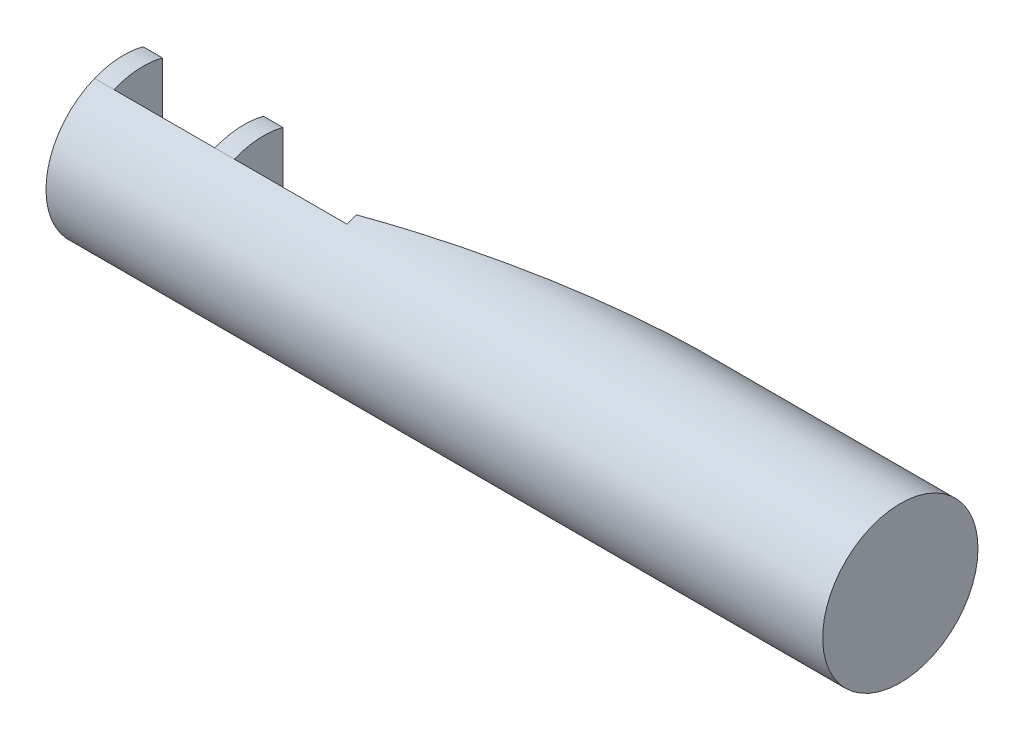
SolidWorks part; units mm, degrees
material "Stainless Steel (ferritic)"
ref_plane "Front Plane" through (0, 0, 0) normal (0, 0, 1) x (1, 0, 0)
ref_plane "Top Plane" through (0, 0, 0) normal (0, 1, 0) x (1, 0, 0)
ref_plane "Right Plane" through (0, 0, 0) normal (1, 0, 0) x (0, 0, -1)
sketch "Sketch2" plane through (0, 0, 0) normal (1, 0, 0) x (0, 0, -1)
  circle A0 centre (0, 0) radius 4
extrude "Boss-Extrude1" add sketch "Sketch2" along normal blind 40
sketch "Sketch4" plane through (0, 0, 0) normal (0, 0, 1) x (1, 0, 0)
  line L0 (0, -4) -> (40, -4) construction
  line L1 (1, 5.3716) -> (6.2, 5.3716)
  line L2 (1, 5.3716) -> (1, -4)
  line L3 (1, -4) -> (6.2, -4)
  line L4 (6.2, 5.3716) -> (6.2, -4)
  line L5 (0, 4) -> (0, -4) construction
  point P8 (1, -4)
  dimension "D1" = 5.2
  dimension "D2" = 1
extrude "Cut-Extrude2" cut sketch "Sketch4" against normal blind 4 and the other way blind 1.5
sketch "Sketch5" plane through (0, 0, 0) normal (-1, 0, 0) x (0, 0, 1)
  circle A0 centre (0.3, 0.2) radius 0.5
  circle A1 centre (0.3, -2.2) radius 0.5
  point P2 (0, 0)
  point P3 (0, 0)
  point P4 (0.0331, 0.2024)
  dimension "D1" = 2.4
extrude "Threads" cut sketch "Sketch5" against normal blind 5
sketch "Sketch6" plane through (0, 0, 0) normal (0, 0, 1) x (1, 0, 0)
  line L1 (7.2, 5.8542) -> (13, 5.8542)
  line L2 (7.2, 5.8542) -> (7.2, -4)
  line L3 (7.2, -4) -> (13, -4)
  line L4 (13, 5.8542) -> (13, -4)
  line L6 (6.2, -3.7081) -> (6.2, 3.7081) construction
  dimension "D1" = 1
extrude "Cut-Extrude4" cut sketch "Sketch6" against normal blind 4 and the other way blind 1.5
sketch "Sketch8" plane through (13, 0, 0) normal (-1, 0, 0) x (0, 0, 1)
  line L1 (1.0029, 10.3807) -> (-9.7606, 10.3807)
  line L2 (1.0029, 10.3807) -> (1.0029, -12.7659)
  line L3 (1.0029, -12.7659) -> (-9.7606, -12.7659)
  line L4 (-9.7606, 10.3807) -> (-9.7606, -12.7659)
  point P4 (-9.3346, 10.3807)
  point P5 (-9.7606, -12.7659)
extrude "Cut-Extrude6" cut sketch "Sketch8" against normal blind 15 draft 15
sketch "Sketch11" plane through (0, 0, 0) normal (-1, 0, 0) x (0, 0, 1)
  line L1 (-1, 4.5803) -> (-4.9964, 4.5803)
  line L2 (-1, 4.5803) -> (-1, -5.1563)
  line L3 (-1, -5.1563) -> (-4.9964, -5.1563)
  line L4 (-4.9964, 4.5803) -> (-4.9964, -5.1563)
  point P4 (-4.3131, 4.5803)
  point P5 (-4.9964, -5.1563)
  dimension "D1" = 1
extrude "Cut-Extrude10" cut sketch "Sketch11" against normal blind 9
